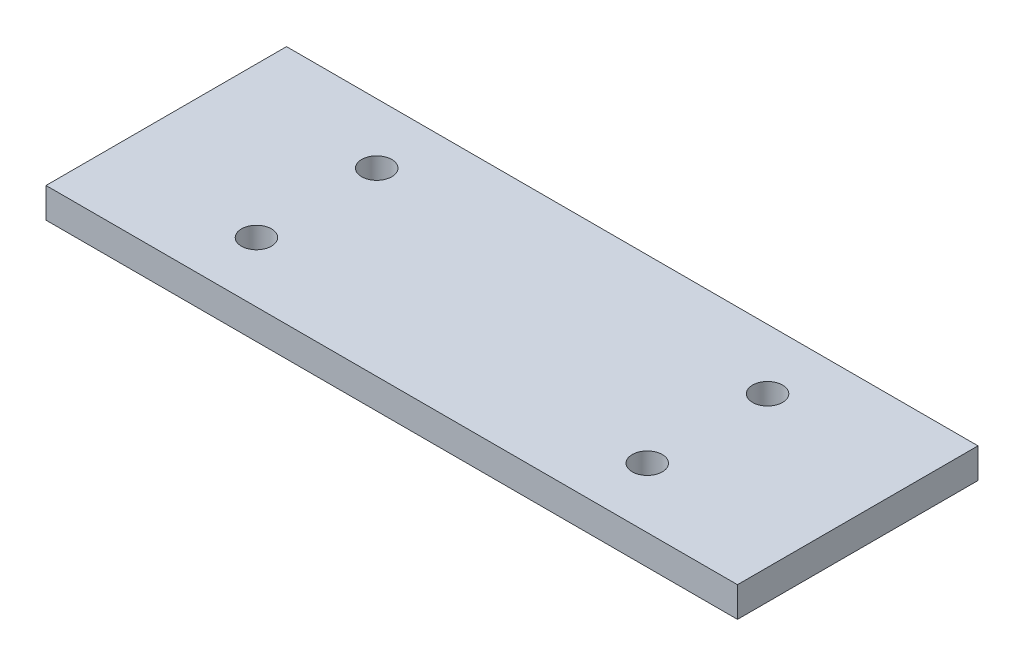
SolidWorks part; units mm, degrees
ref_plane "Front Plane" through (0, 0, 0) normal (0, 0, 1) x (1, 0, 0)
ref_plane "Top Plane" through (0, 0, 0) normal (0, 1, 0) x (1, 0, 0)
ref_plane "Right Plane" through (0, 0, 0) normal (1, 0, 0) x (0, 0, -1)
sketch "Sketch1" plane through (0, 0, 0) normal (0, 1, 0) x (1, 0, 0)
  line L0 (0, 44.9063) -> (0, -59.4885) construction
  line L1 (-57.5, 20) -> (57.5, 20)
  line L2 (-57.5, 20) -> (-57.5, -20)
  line L3 (-57.5, -20) -> (57.5, -20)
  line L4 (57.5, 20) -> (57.5, -20)
  line L5 (-57.5, 20) -> (57.5, -20) construction
  line L6 (-57.5, -20) -> (57.5, 20) construction
  line L7 (-85.3386, 0) -> (95.7781, 0) construction
  circle A0 centre (-32.5, 10) radius 2.5
  circle A1 centre (-32.5, -10) radius 2.5
  circle A2 centre (32.5, -10) radius 2.5
  circle A3 centre (32.5, 10) radius 2.5
  point P0 (0, 0)
  dimension "D3" = 5
  dimension "D1" = 115
  dimension "D2" = 40
  dimension "D4" = 10
  dimension "D5" = 65
extrude "Boss-Extrude1" add sketch "Sketch1" along normal blind 5
